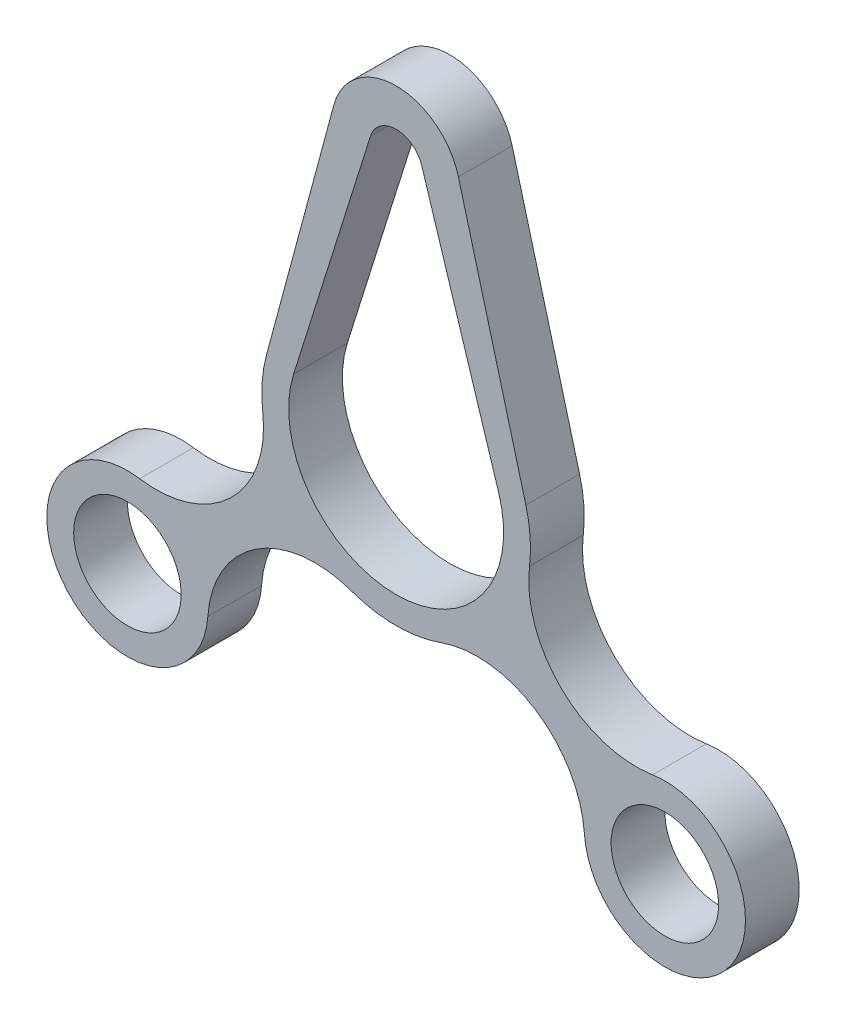
SolidWorks part; units mm, degrees
ref_plane "Front Plane" through (0, 0, 0) normal (0, 0, 1) x (1, 0, 0)
ref_plane "Top Plane" through (0, 0, 0) normal (0, 1, 0) x (1, 0, 0)
ref_plane "Right Plane" through (0, 0, 0) normal (1, 0, 0) x (0, 0, -1)
sketch "Sketch1" plane through (0, 0, 0) normal (0, 0, 1) x (1, 0, 0)
  line L0 (0, 0) -> (0, 50000) construction
  line L1 (-2.7094, 0) -> (-50002.7094, 0) construction
  line L2 (-11.5873, 53.12) -> (-24.1402, 6.5)
  line L3 (-4.7697, 51.5) -> (-19.0788, 6)
  line L4 (11.5873, 53.12) -> (24.1402, 6.5)
  line L5 (4.7697, 51.5) -> (19.0788, 6)
  arc A0 (-19.0788, 6) -> (19.0788, 6) centre (0, 0) ccw
  arc A1 (-24.1402, 6.5) -> (-24.8188, -3.0042) centre (0, 0) ccw
  circle A2 centre (50, -40) radius 10
  arc A3 (35.0352, -41.0274) -> (47.7174, -25.1747) centre (50, -40) ccw
  arc A4 (8.379, -23.554) -> (35.0352, -41.0274) centre (15.0822, -42.3973) cw
  arc A5 (24.8188, -3.0042) -> (47.7174, -25.1747) centre (44.6739, -5.4076) ccw
  circle A6 centre (-50, -40) radius 10
  arc A7 (-35.0352, -41.0274) -> (-47.7174, -25.1747) centre (-50, -40) cw
  arc A8 (-8.379, -23.554) -> (-35.0352, -41.0274) centre (-15.0822, -42.3973) ccw
  arc A9 (-24.8188, -3.0042) -> (-47.7174, -25.1747) centre (-44.6739, -5.4076) cw
  arc A10 (4.7697, 51.5) -> (-4.7697, 51.5) centre (0, 50) ccw
  arc A11 (11.5873, 53.12) -> (-11.5873, 53.12) centre (0, 50) ccw
  arc A12 (24.8188, -3.0042) -> (24.1402, 6.5) centre (0, 0) ccw
  arc A13 (-8.379, -23.554) -> (8.379, -23.554) centre (0, 0) ccw
  dimension "D1" = 40
  dimension "D2" = 50
  dimension "D3" = 20
  dimension "D4" = 30
  dimension "D7" = 20
  dimension "D8" = 20
  dimension "D9" = 10
  dimension "D10" = 24
  dimension "D5" = 50
  dimension "D6" = 40
  dimension "D11" = 50
extrude "Boss-Extrude1" add sketch "Sketch1" along normal mid plane 10
